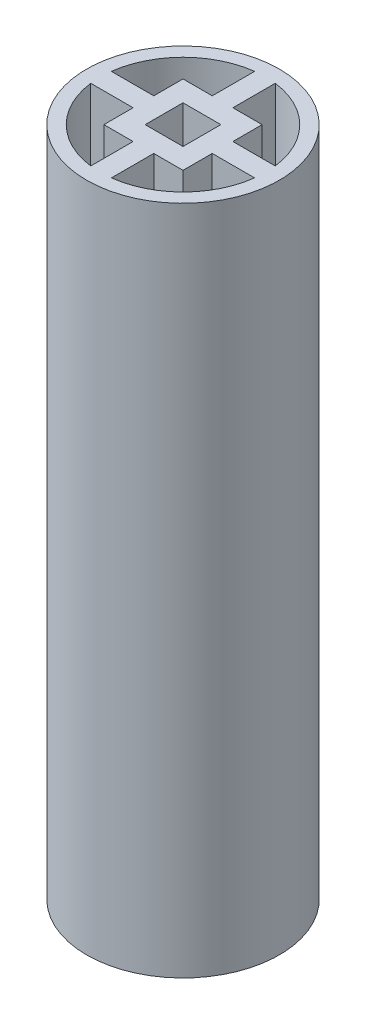
SolidWorks part; units mm, degrees
ref_plane "Front Plane" through (0, 0, 0) normal (0, 0, 1) x (1, 0, 0)
ref_plane "Top Plane" through (0, 0, 0) normal (0, 1, 0) x (1, 0, 0)
ref_plane "Right Plane" through (0, 0, 0) normal (1, 0, 0) x (0, 0, -1)
sketch "Sketch1" plane through (0, 0, 0) normal (0, 1, 0) x (1, 0, 0)
  line L0 (-5.75, 1.5) -> (-11.9059, 1.5)
  line L1 (5.75, -5.75) -> (1.5, -5.75)
  line L2 (5.75, -5.75) -> (5.75, -1.5)
  line L3 (5.75, 5.75) -> (1.5, 5.75)
  line L4 (-5.75, -5.75) -> (-5.75, -1.5)
  line L5 (5.75, -5.75) -> (-5.75, 5.75) construction
  line L6 (5.75, 5.75) -> (-5.75, -5.75) construction
  line L7 (-11.9059, -1.5) -> (-5.75, -1.5)
  line L8 (1.5, 5.75) -> (1.5, 11.9059)
  line L9 (-1.5, 11.9059) -> (-1.5, 5.75)
  line L10 (5.75, -1.5) -> (11.9059, -1.5)
  line L11 (11.9059, 1.5) -> (5.75, 1.5)
  line L12 (-1.5, -5.75) -> (-1.5, -11.9059)
  line L13 (1.5, -11.9059) -> (1.5, -5.75)
  line L14 (-5.75, 1.5) -> (-5.75, 5.75)
  line L15 (-1.5, 5.75) -> (-5.75, 5.75)
  line L16 (5.75, 1.5) -> (5.75, 5.75)
  line L17 (-1.5, -5.75) -> (-5.75, -5.75)
  line L19 (2.75, -2.75) -> (-2.75, -2.75)
  line L20 (2.75, -2.75) -> (2.75, 2.75)
  line L21 (2.75, 2.75) -> (-2.75, 2.75)
  line L22 (-2.75, -2.75) -> (-2.75, 2.75)
  line L23 (2.75, -2.75) -> (-2.75, 2.75) construction
  line L24 (2.75, 2.75) -> (-2.75, -2.75) construction
  circle A0 centre (0, 0) radius 14
  arc A1 (-11.9059, -1.5) -> (-1.5, -11.9059) centre (0, 0) ccw
  arc A3 (-1.5, 11.9059) -> (-11.9059, 1.5) centre (0, 0) ccw
  arc A4 (11.9059, 1.5) -> (1.5, 11.9059) centre (0, 0) ccw
  arc A5 (1.5, -11.9059) -> (11.9059, -1.5) centre (0, 0) ccw
  point P28 (0, 0)
  dimension "D1" = 28
  dimension "D2" = 2
  dimension "D4" = 5.5
  dimension "D3" = 11.5
  dimension "D5" = 3
  dimension "D6" = 1.5
  dimension "D7" = 4
extrude "Body" add sketch "Sketch1" along normal mid plane 97.5
